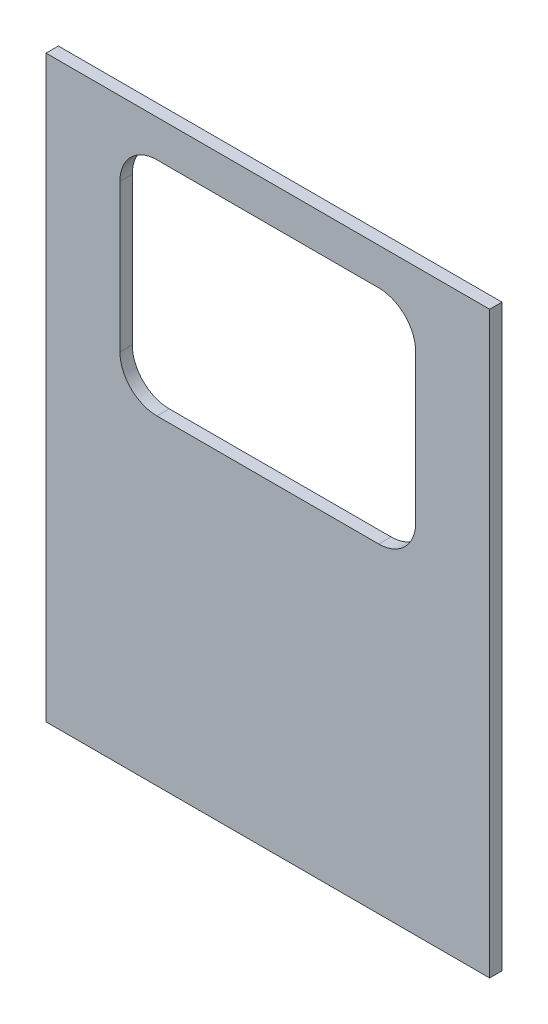
SolidWorks part; units mm, degrees
material "ABS PC"
ref_plane "Front Plane" through (0, 0, 0) normal (0, 0, 1) x (1, 0, 0)
ref_plane "Top Plane" through (0, 0, 0) normal (0, 1, 0) x (1, 0, 0)
ref_plane "Right Plane" through (0, 0, 0) normal (1, 0, 0) x (0, 0, -1)
sketch "Sketch1" plane through (0, 0, 0) normal (0, 0, 1) x (1, 0, 0)
  line L1 (-457.2, 596.9) -> (457.2, 596.9)
  line L2 (-457.2, 596.9) -> (-457.2, -596.9)
  line L3 (-457.2, -596.9) -> (457.2, -596.9)
  line L4 (457.2, 596.9) -> (457.2, -596.9)
  line L5 (-457.2, 596.9) -> (457.2, -596.9) construction
  line L6 (-457.2, -596.9) -> (457.2, 596.9) construction
  line L7 (-304.8, 520.7) -> (304.8, 520.7)
  line L8 (-304.8, 520.7) -> (-304.8, 63.5)
  line L9 (-304.8, 63.5) -> (304.8, 63.5)
  line L10 (304.8, 520.7) -> (304.8, 63.5)
  line L11 (-304.8, 520.7) -> (304.8, 63.5) construction
  line L12 (-304.8, 63.5) -> (304.8, 520.7) construction
  point P0 (0, 0)
  point P6 (0, 292.1)
  dimension "D1" = 457.2
  dimension "D2" = 609.6
  dimension "D3" = 660.4
  dimension "D4" = 76.2
  dimension "D5" = 914.4
extrude "Boss-Extrude1" add sketch "Sketch1" along normal blind 25.4
fillet "Fillet1" radius 76.2 4 edges at (304.8, 520.7, 12.7) (-304.8, 520.7, 12.7) (304.8, 63.5, 12.7) (-304.8, 63.5, 12.7)
